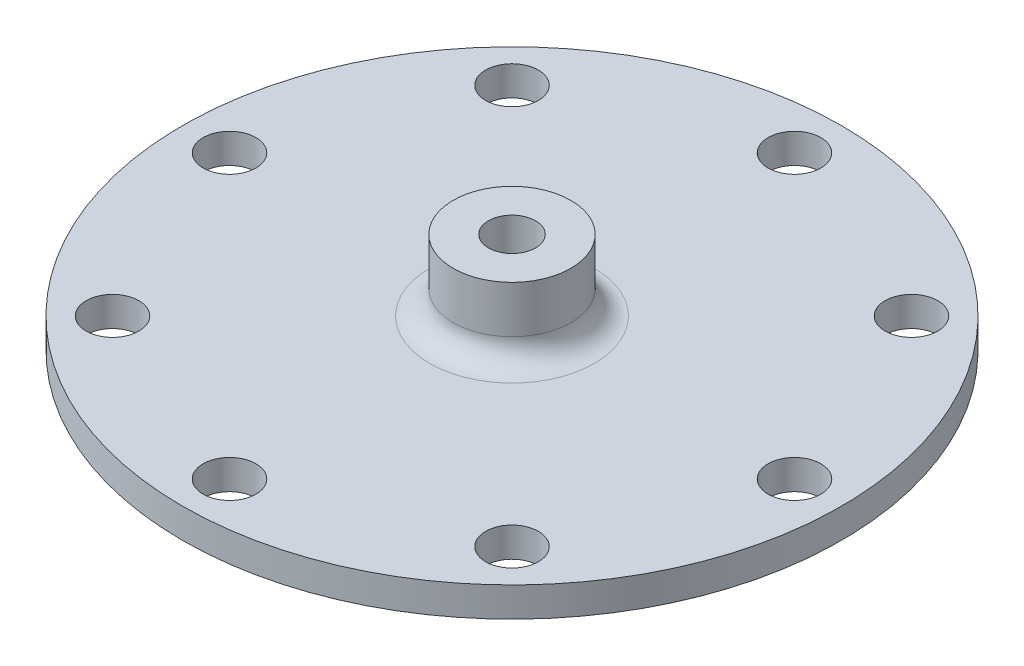
SolidWorks part; units mm, degrees
ref_plane "Front Plane" through (0, 0, 0) normal (0, 0, 1) x (1, 0, 0)
ref_plane "Top Plane" through (0, 0, 0) normal (0, 1, 0) x (1, 0, 0)
ref_plane "Right Plane" through (0, 0, 0) normal (1, 0, 0) x (0, 0, -1)
sketch "Sketch1" plane through (0, 0, 0) normal (0, 1, 0) x (1, 0, 0)
  circle A0 centre (0, 0) radius 22.225
  dimension "D1" = 44.45
extrude "Boss-Extrude1" add sketch "Sketch1" along normal blind 2
sketch "Sketch2" plane through (0, 2, 0) normal (0, 1, 0) x (1, 0, 0)
  circle A0 centre (0, 19.05) radius 1.778
  circle A1 centre (13.4704, 13.4704) radius 1.778
  circle A2 centre (19.05, 0) radius 1.778
  circle A3 centre (13.4704, -13.4704) radius 1.778
  circle A4 centre (0, -19.05) radius 1.778
  circle A5 centre (-13.4704, -13.4704) radius 1.778
  circle A6 centre (-19.05, 0) radius 1.778
  circle A7 centre (-13.4704, 13.4704) radius 1.778
  point P20 (0, 0)
  dimension "D1" = 3.556
  dimension "D2" = 19.05
  dimension "D3" = 8
extrude "Cut-Extrude1" cut sketch "Sketch2" against normal through all
sketch "Sketch3" plane through (0, 2, 0) normal (0, 1, 0) x (1, 0, 0)
  circle A0 centre (0, 0) radius 3.9688
  dimension "D1" = 7.9375
extrude "Boss-Extrude2" add sketch "Sketch3" along normal blind 4.7625
sketch "Sketch4" plane through (0, 6.7625, 0) normal (0, 1, 0) x (1, 0, 0)
  circle A0 centre (0, 0) radius 1.5875
  dimension "D1" = 3.175
extrude "Cut-Extrude2" cut sketch "Sketch4" against normal up to surface (4.7625 mm away) up to face at (0, 2, 3.9688)
fillet "Fillet1" radius 1.5875 1 edges at (0, 2, 3.9688)
sketch "Sketch5" plane through (0, 0, 0) normal (0, -1, 0) x (-1, 0, 0)
  circle A0 centre (0, 0) radius 0.7937
extrude "Cut-Extrude6" cut sketch "Sketch5" against normal blind 2.54
